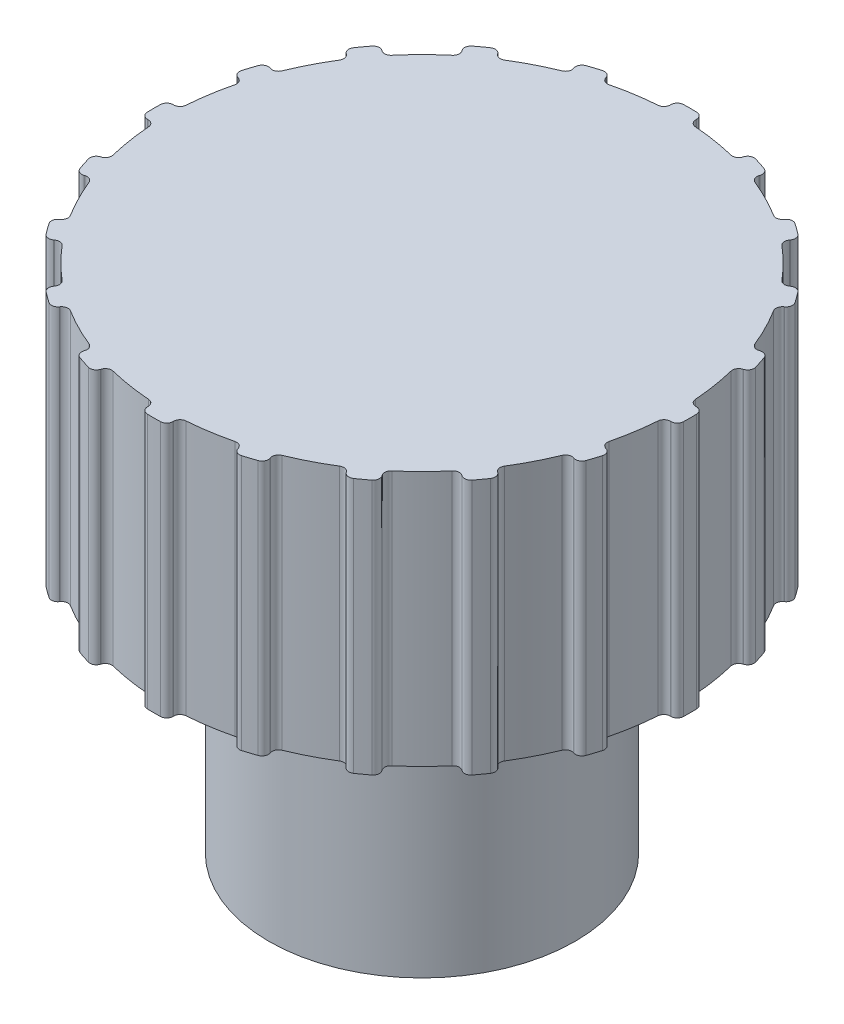
SolidWorks part; units mm, degrees
ref_plane "Front Plane" through (0, 0, 0) normal (0, 0, 1) x (1, 0, 0)
ref_plane "Top Plane" through (0, 0, 0) normal (0, 1, 0) x (1, 0, 0)
ref_plane "Right Plane" through (0, 0, 0) normal (1, 0, 0) x (0, 0, -1)
sketch "Sketch1" plane through (0, 0, 0) normal (0, 1, 0) x (1, 0, 0)
  circle A0 centre (0, 0) radius 6
  circle A2 centre (0, 0) radius 4.1
  dimension "D1" = 8.2
  dimension "D2" = 12
extrude "Boss-Extrude1" add sketch "Sketch1" along normal blind 10
sketch "Sketch2" plane through (0, 10, 0) normal (0, 1, 0) x (1, 0, 0)
  circle A0 centre (0, 0) radius 10
  dimension "D1" = 20
extrude "Boss-Extrude2" add sketch "Sketch2" along normal blind 10
ref_plane "Plane1" through (-10, 0, 0) normal (-1, 0, 0) x (0, 0, 1)
sketch "Sketch4" plane through (0, 20, 0) normal (0, 1, 0) x (1, 0, 0)
  line L0 (0, -1000) -> (0, 49000) construction
  line L1 (0.5, 10.4881) -> (0.5, 9.9875)
  line L2 (-0.5, 10.4881) -> (-0.5, 9.9875)
  arc A0 (0.5, 10.4881) -> (-0.5, 10.4881) centre (0, 0) ccw
  circle A1 centre (0, 0) radius 10
  arc A2 (0.5, 9.9875) -> (-0.5, 9.9875) centre (0, 0) ccw
  circle A3 centre (0, 0) radius 10.5 construction
  circle A4 centre (0, 0) radius 10 construction
  dimension "D3" = 0.5
  dimension "D1" = 0
  dimension "D2" = 0.5
extrude "Boss-Extrude4" add sketch "Sketch4" against normal up to surface (10 mm away) up to face at (0, 10, 6)
fillet "Fillet2" radius 0.25 4 edges at (-0.5, 15, -10.4881) (0.5, 15, -10.4881) (-0.5, 15, -9.9875) (0.5, 15, -9.9875)
fillet "Fillet3" radius 2 1 edges at (0, 10, 6)
pattern_circular "CirPattern2" count 20 over 360 about axis through (0, 0, 0) along (0, 1, 0) of "Boss-Extrude4", "Fillet2"
